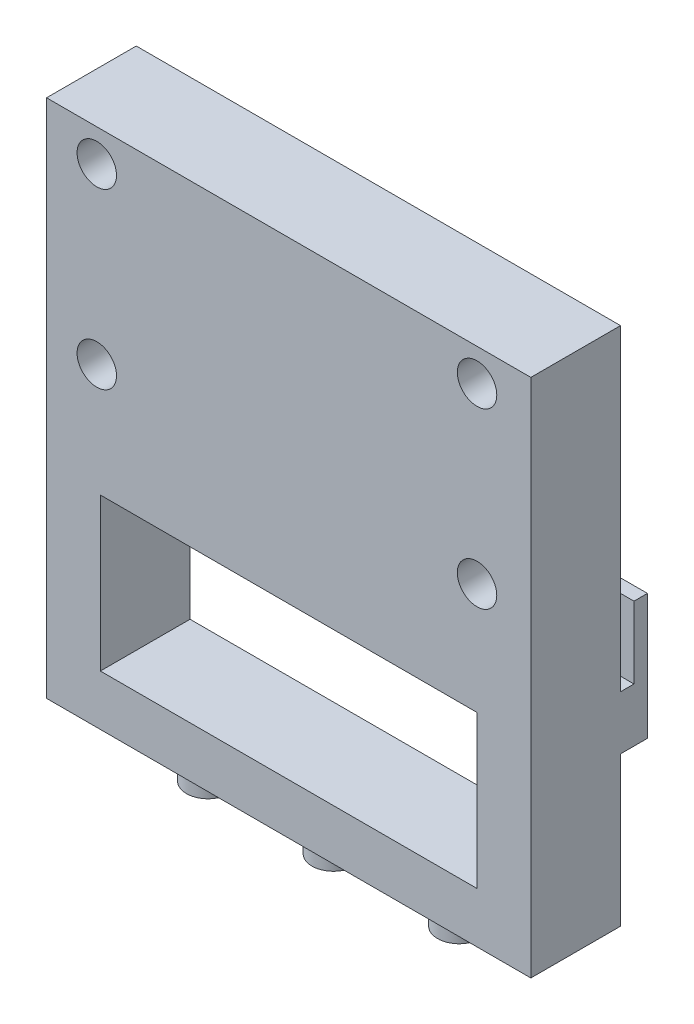
SolidWorks part; units mm, degrees
ref_plane "Front Plane" through (0, 0, 0) normal (0, 0, 1) x (1, 0, 0)
ref_plane "Top Plane" through (0, 0, 0) normal (0, 1, 0) x (1, 0, 0)
ref_plane "Right Plane" through (0, 0, 0) normal (1, 0, 0) x (0, 0, -1)
sketch "Sketch1" plane through (0, 0, 0) normal (0, 0, 1) x (1, 0, 0)
  line L1 (-13.5, 14.5) -> (13.5, 14.5)
  line L2 (-13.5, 14.5) -> (-13.5, -14.5)
  line L3 (-13.5, -14.5) -> (13.5, -14.5)
  line L4 (13.5, 14.5) -> (13.5, -14.5)
  line L5 (-13.5, 14.5) -> (13.5, -14.5) construction
  line L6 (-13.5, -14.5) -> (13.5, 14.5) construction
  point P0 (0, 0)
  dimension "D1" = 27
  dimension "D2" = 29
extrude "Boss-Extrude1" add sketch "Sketch1" along normal blind 5
sketch "Sketch2" plane through (0, -14.5, 0) normal (0, -1, 0) x (1, 0, 0)
  line L0 (-13.5, 2.5) -> (13.5, 2.5) construction
  line L1 (-13.5, 5) -> (-13.5, 0) construction
  line L2 (13.5, 5) -> (13.5, 0) construction
  circle A0 centre (-7, 2.5) radius 1.2
  circle A1 centre (0, 2.5) radius 1.2
  circle A2 centre (7, 2.5) radius 1.2
  point P13 (13.5, 2.5)
  dimension "D1" = 2.4
  dimension "D2" = 7
  dimension "D3" = 7
sketch "Sketch3" plane through (0, 0, 5) normal (0, 0, 1) x (1, 0, 0)
  line L0 (0, 14.5) -> (0, -14.5) construction
  line L1 (13.5, 14.5) -> (-13.5, 14.5) construction
  line L2 (-13.5, -14.5) -> (13.5, -14.5) construction
  line L3 (-13.5, 0) -> (13.5, 0) construction
  line L4 (-13.5, 14.5) -> (-13.5, -14.5) construction
  line L5 (13.5, -14.5) -> (13.5, 14.5) construction
  line L6 (-12.5, 15.7476) -> (12.5, 15.7476) construction
  line L7 (-13.5, -9.36) -> (13.5, -9.36) construction
  line L8 (-5.4, 5.4) -> (5.4, 5.4) construction
  line L9 (-5.4, 5.4) -> (-5.4, -5.4) construction
  line L10 (-5.4, -5.4) -> (5.4, -5.4) construction
  line L11 (5.4, 5.4) -> (5.4, -5.4) construction
  line L12 (-5.4, 5.4) -> (5.4, -5.4) construction
  line L13 (-5.4, -5.4) -> (5.4, 5.4) construction
  line L14 (-10.7, 5.4) -> (-10.7, 0.65) construction
  circle A0 centre (-10.7, 12.7) radius 1.1
  circle A1 centre (10.5, 12.7) radius 1.1
  circle A2 centre (-10.7, 12.7) radius 2.375 construction
  circle A3 centre (-10.7, 3.025) radius 2.375 construction
  circle A4 centre (-10.7, 3.025) radius 1.1
  circle A5 centre (10.5, 3.025) radius 1.1
  circle A6 centre (0, 0) radius 3.475 construction
  point P22 (0, 15.7476)
  point P24 (0, 0)
  dimension "D1" = 2.2
  dimension "D5" = 4.75
  dimension "D6" = 4.75
  dimension "D8" = 2.2
  dimension "D13" = 6.95
  dimension "D7" = 7.3
  dimension "D2" = 1.8
  dimension "D3" = 1.8
  dimension "D4" = 2
  dimension "D9" = 10.8
  dimension "D10" = 25
  dimension "D11" = 10.8
  dimension "D12" = 7.3
  dimension "D14" = 23.86
  dimension "D15" = 14.5
  dimension "D16" = 21.2
  dimension "D17" = 9.675
  dimension "D18" = 9.36
  dimension "D19" = 14.5
extrude "Cut-Extrude2" cut sketch "Sketch3" against normal blind 10
sketch "Sketch4" plane through (0, 0, 5) normal (0, 0, 1) x (1, 0, 0)
  line L0 (0, 14.5) -> (0, -14.5) construction
  line L1 (13.5, 14.5) -> (-13.5, 14.5) construction
  line L2 (-13.5, -14.5) -> (13.5, -14.5) construction
  line L4 (-10.5, -3.1791) -> (10.5, -3.1791)
  line L5 (-10.5, -3.1791) -> (-10.5, -11.6791)
  line L6 (-10.5, -11.6791) -> (10.5, -11.6791)
  line L7 (10.5, -3.1791) -> (10.5, -11.6791)
  line L8 (-10.5, -3.1791) -> (10.5, -11.6791) construction
  line L9 (-10.5, -11.6791) -> (10.5, -3.1791) construction
  point P6 (0, -7.4291)
  dimension "D1" = 21
  dimension "D2" = 8.5
extrude "Cut-Extrude3" cut sketch "Sketch4" against normal blind 10
extrude "Boss-Extrude2" add sketch "Sketch2" along normal blind 2
sketch "Sketch7" plane through (0, 0, 0) normal (0, 0, -1) x (-1, 0, 0)
  line L0 (-13.5, -3.1791) -> (18.6354, -3.1791) construction
  line L1 (-13.5, -14.5) -> (-13.5, 14.5) construction
  line L2 (-13.5, -3.1791) -> (-13.5, -6.1791)
  line L3 (-13.5, -6.1791) -> (-10.5, -6.1791)
  line L4 (-10.5, -11.6791) -> (-10.5, -3.1791) construction
  line L5 (-10.5, -6.1791) -> (-10.5, -3.1791)
  line L6 (0, 14.5) -> (0, -18.3813) construction
  line L7 (-13.5, 14.5) -> (13.5, 14.5) construction
  line L8 (10.5, -6.1791) -> (10.5, -3.1791)
  line L9 (13.5, -6.1791) -> (10.5, -6.1791)
  line L10 (13.5, -3.1791) -> (13.5, -6.1791)
  line L11 (-13.5, -3.1791) -> (-10.5, -3.1791)
  line L12 (10.5, -3.1791) -> (13.5, -3.1791)
  dimension "D1" = 3
extrude "Boss-Extrude5" add sketch "Sketch7" along normal blind 1.5
sketch "Sketch8" plane through (0, -3.1791, 0) normal (0, 1, 0) x (1, 0, 0)
  line L0 (13.5, 1.5) -> (13.5, 0) construction
  line L1 (-13.5, 1.5) -> (13.5, 1.5)
  line L2 (-13.5, 1.5) -> (-13.5, 0.75)
  line L3 (-13.5, 0.75) -> (13.5, 0.75)
  line L4 (13.5, 1.5) -> (13.5, 0.75)
extrude "Boss-Extrude6" add sketch "Sketch8" along normal blind 4
